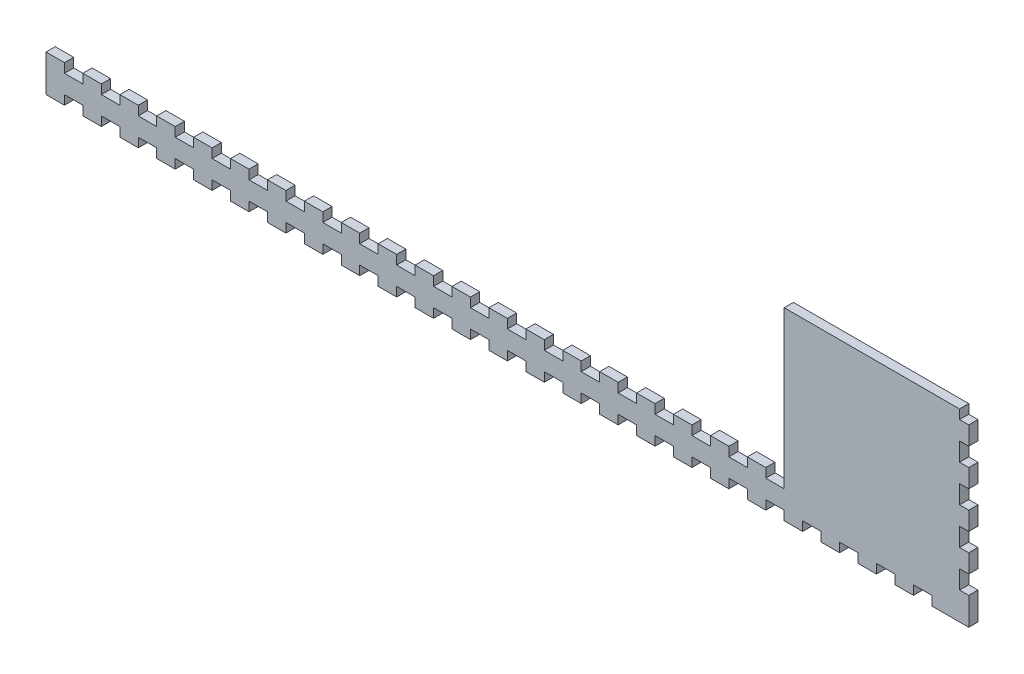
SolidWorks part; units mm, degrees
ref_plane "Plan de face" through (0, 0, 0) normal (0, 0, 1) x (1, 0, 0)
ref_plane "Plan de dessus" through (0, 0, 0) normal (0, 1, 0) x (1, 0, 0)
ref_plane "Plan de droite" through (0, 0, 0) normal (1, 0, 0) x (0, 0, -1)
sketch "Esquisse1" plane through (0, 0, 0) normal (0, 0, 1) x (1, 0, 0)
  line L0 (-250, 10) -> (150, 10)
  line L1 (-250, -10) -> (250, -10)
  line L2 (-250, -10) -> (-250, 10)
  line L4 (250, -10) -> (250, 10)
  line L5 (-250, -10) -> (250, 10) construction
  line L6 (-250, 10) -> (250, -10) construction
  line L8 (250, 10) -> (250, 90)
  line L9 (250, 90) -> (150, 90)
  line L10 (150, 10) -> (150, 90)
  point P0 (0, 0)
  dimension "D1" = 20
  dimension "D2" = 500
  dimension "D3" = 100
  dimension "D4" = 80
extrude "Boss.-Extru.1" add sketch "Esquisse1" along normal blind 5
sketch "Esquisse2" plane through (0, 0, 5) normal (0, 0, 1) x (1, 0, 0)
  line L3 (-240, 5) -> (-230, 5)
  line L4 (-230, 10) -> (-230, 5)
  line L5 (-250, -10) -> (250, -10) construction
  line L6 (-240, -10) -> (-230, -10)
  line L7 (-240, -10) -> (-240, -5)
  line L8 (-240, -5) -> (-230, -5)
  line L9 (-230, -10) -> (-230, -5)
  line L10 (-220, 10) -> (-220, 5)
  line L11 (-220, 10) -> (-210, 10)
  line L12 (-210, 10) -> (-210, 5)
  line L13 (-220, 5) -> (-210, 5)
  line L14 (-220, -10) -> (-220, -5)
  line L15 (-220, -10) -> (-210, -10)
  line L16 (-210, -10) -> (-210, -5)
  line L17 (-220, -5) -> (-210, -5)
  line L18 (-200, 10) -> (-200, 5)
  line L19 (-200, 10) -> (-190, 10)
  line L20 (-190, 10) -> (-190, 5)
  line L21 (-200, 5) -> (-190, 5)
  line L22 (-200, -10) -> (-200, -5)
  line L23 (-200, -10) -> (-190, -10)
  line L24 (-190, -10) -> (-190, -5)
  line L25 (-200, -5) -> (-190, -5)
  line L26 (-180, 10) -> (-180, 5)
  line L27 (-180, 10) -> (-170, 10)
  line L28 (-170, 10) -> (-170, 5)
  line L29 (-180, 5) -> (-170, 5)
  line L30 (-180, -10) -> (-180, -5)
  line L31 (-180, -10) -> (-170, -10)
  line L32 (-170, -10) -> (-170, -5)
  line L33 (-180, -5) -> (-170, -5)
  line L34 (-160, 10) -> (-160, 5)
  line L35 (-160, 10) -> (-150, 10)
  line L36 (-150, 10) -> (-150, 5)
  line L37 (-160, 5) -> (-150, 5)
  line L38 (-160, -10) -> (-160, -5)
  line L39 (-160, -10) -> (-150, -10)
  line L40 (-150, -10) -> (-150, -5)
  line L41 (-160, -5) -> (-150, -5)
  line L42 (-140, 10) -> (-140, 5)
  line L43 (-140, 10) -> (-130, 10)
  line L44 (-130, 10) -> (-130, 5)
  line L45 (-140, 5) -> (-130, 5)
  line L46 (-140, -10) -> (-140, -5)
  line L47 (-140, -10) -> (-130, -10)
  line L48 (-130, -10) -> (-130, -5)
  line L49 (-140, -5) -> (-130, -5)
  line L50 (-120, 10) -> (-120, 5)
  line L51 (-120, 10) -> (-110, 10)
  line L52 (-110, 10) -> (-110, 5)
  line L53 (-120, 5) -> (-110, 5)
  line L54 (-120, -10) -> (-120, -5)
  line L55 (-120, -10) -> (-110, -10)
  line L56 (-110, -10) -> (-110, -5)
  line L57 (-120, -5) -> (-110, -5)
  line L58 (-100, 10) -> (-100, 5)
  line L59 (-100, 10) -> (-90, 10)
  line L60 (-90, 10) -> (-90, 5)
  line L61 (-100, 5) -> (-90, 5)
  line L62 (-100, -10) -> (-100, -5)
  line L63 (-100, -10) -> (-90, -10)
  line L64 (-90, -10) -> (-90, -5)
  line L65 (-100, -5) -> (-90, -5)
  line L66 (-80, 10) -> (-80, 5)
  line L67 (-80, 10) -> (-70, 10)
  line L68 (-70, 10) -> (-70, 5)
  line L69 (-80, 5) -> (-70, 5)
  line L70 (-80, -10) -> (-80, -5)
  line L71 (-80, -10) -> (-70, -10)
  line L72 (-70, -10) -> (-70, -5)
  line L73 (-80, -5) -> (-70, -5)
  line L74 (-60, 10) -> (-60, 5)
  line L75 (-60, 10) -> (-50, 10)
  line L76 (-50, 10) -> (-50, 5)
  line L77 (-60, 5) -> (-50, 5)
  line L78 (-60, -10) -> (-60, -5)
  line L79 (-60, -10) -> (-50, -10)
  line L80 (-50, -10) -> (-50, -5)
  line L81 (-60, -5) -> (-50, -5)
  line L82 (-40, 10) -> (-40, 5)
  line L83 (-40, 10) -> (-30, 10)
  line L84 (-30, 10) -> (-30, 5)
  line L85 (-40, 5) -> (-30, 5)
  line L86 (-40, -10) -> (-40, -5)
  line L87 (-40, -10) -> (-30, -10)
  line L88 (-30, -10) -> (-30, -5)
  line L89 (-40, -5) -> (-30, -5)
  line L90 (-20, 10) -> (-20, 5)
  line L91 (-20, 10) -> (-10, 10)
  line L92 (-10, 10) -> (-10, 5)
  line L93 (-20, 5) -> (-10, 5)
  line L94 (-20, -10) -> (-20, -5)
  line L95 (-20, -10) -> (-10, -10)
  line L96 (-10, -10) -> (-10, -5)
  line L97 (-20, -5) -> (-10, -5)
  line L98 (0, 10) -> (0, 5)
  line L99 (0, 10) -> (10, 10)
  line L100 (10, 10) -> (10, 5)
  line L101 (0, 5) -> (10, 5)
  line L102 (0, -10) -> (0, -5)
  line L103 (0, -10) -> (10, -10)
  line L104 (10, -10) -> (10, -5)
  line L105 (0, -5) -> (10, -5)
  line L106 (20, 10) -> (20, 5)
  line L107 (20, 10) -> (30, 10)
  line L108 (30, 10) -> (30, 5)
  line L109 (20, 5) -> (30, 5)
  line L110 (20, -10) -> (20, -5)
  line L111 (20, -10) -> (30, -10)
  line L112 (30, -10) -> (30, -5)
  line L113 (20, -5) -> (30, -5)
  line L114 (40, 10) -> (40, 5)
  line L115 (40, 10) -> (50, 10)
  line L116 (50, 10) -> (50, 5)
  line L117 (40, 5) -> (50, 5)
  line L118 (40, -10) -> (40, -5)
  line L119 (40, -10) -> (50, -10)
  line L120 (50, -10) -> (50, -5)
  line L121 (40, -5) -> (50, -5)
  line L122 (60, 10) -> (60, 5)
  line L123 (60, 10) -> (70, 10)
  line L124 (70, 10) -> (70, 5)
  line L125 (60, 5) -> (70, 5)
  line L126 (60, -10) -> (60, -5)
  line L127 (60, -10) -> (70, -10)
  line L128 (70, -10) -> (70, -5)
  line L129 (60, -5) -> (70, -5)
  line L130 (80, 10) -> (80, 5)
  line L131 (80, 10) -> (90, 10)
  line L132 (90, 10) -> (90, 5)
  line L133 (80, 5) -> (90, 5)
  line L134 (80, -10) -> (80, -5)
  line L135 (80, -10) -> (90, -10)
  line L136 (90, -10) -> (90, -5)
  line L137 (80, -5) -> (90, -5)
  line L138 (100, 10) -> (100, 5)
  line L139 (100, 10) -> (110, 10)
  line L140 (110, 10) -> (110, 5)
  line L141 (100, 5) -> (110, 5)
  line L142 (100, -10) -> (100, -5)
  line L143 (100, -10) -> (110, -10)
  line L144 (110, -10) -> (110, -5)
  line L145 (100, -5) -> (110, -5)
  line L146 (120, 10) -> (120, 5)
  line L147 (120, 10) -> (130, 10)
  line L148 (130, 10) -> (130, 5)
  line L149 (120, 5) -> (130, 5)
  line L150 (120, -10) -> (120, -5)
  line L151 (120, -10) -> (130, -10)
  line L152 (130, -10) -> (130, -5)
  line L153 (120, -5) -> (130, -5)
  line L154 (140, 10) -> (140, 5)
  line L155 (140, 10) -> (150, 10)
  line L156 (150, 10) -> (150, 5)
  line L157 (140, 5) -> (150, 5)
  line L158 (140, -10) -> (140, -5)
  line L159 (140, -10) -> (150, -10)
  line L160 (150, -10) -> (150, -5)
  line L161 (140, -5) -> (150, -5)
  line L162 (160, -5) -> (170, -5)
  line L163 (160, -10) -> (160, -5)
  line L164 (170, -10) -> (170, -5)
  line L165 (160, -10) -> (170, -10)
  line L166 (180, -5) -> (190, -5)
  line L167 (180, -10) -> (180, -5)
  line L168 (190, -10) -> (190, -5)
  line L169 (180, -10) -> (190, -10)
  line L170 (200, -5) -> (210, -5)
  line L171 (200, -10) -> (200, -5)
  line L172 (210, -10) -> (210, -5)
  line L173 (200, -10) -> (210, -10)
  line L174 (220, -5) -> (230, -5)
  line L175 (220, -10) -> (220, -5)
  line L176 (230, -10) -> (230, -5)
  line L177 (220, -10) -> (230, -10)
  line L178 (-250, 10) -> (-250, -10) construction
  line L180 (-240, 5) -> (-240, 10)
  line L181 (150, 10) -> (-250, 10) construction
  line L182 (-240, 10) -> (-230, 10)
  line L183 (250, -10) -> (250, 90) construction
  line L184 (250, 5) -> (245, 5)
  line L185 (250, 5) -> (250, 15)
  line L186 (250, 15) -> (245, 15)
  line L187 (245, 5) -> (245, 15)
  line L188 (-250, -10) -> (250, -10) construction
  line L189 (250, 25) -> (250, 35)
  line L190 (250, 25) -> (245, 25)
  line L191 (245, 25) -> (245, 35)
  line L192 (250, 35) -> (245, 35)
  line L193 (250, 45) -> (250, 55)
  line L194 (250, 45) -> (245, 45)
  line L195 (245, 45) -> (245, 55)
  line L196 (250, 55) -> (245, 55)
  line L197 (250, 65) -> (250, 75)
  line L198 (250, 65) -> (245, 65)
  line L199 (245, 65) -> (245, 75)
  line L200 (250, 75) -> (245, 75)
  line L201 (250, 85) -> (250, 95)
  line L202 (250, 85) -> (245, 85)
  line L203 (245, 85) -> (245, 95)
  line L204 (250, 95) -> (245, 95)
  dimension "D1" = 10
  dimension "D2" = 10
  dimension "D3" = 5
  dimension "D4" = 5
  dimension "D5" = 20
  dimension "D7" = 10
  dimension "D8" = 15
  dimension "D9" = 5
  dimension "D10" = 10
  dimension "D6" = 5
  dimension "D11" = 5
extrude "Enlèv. mat.-Extru.2" cut sketch "Esquisse2" against normal through all
